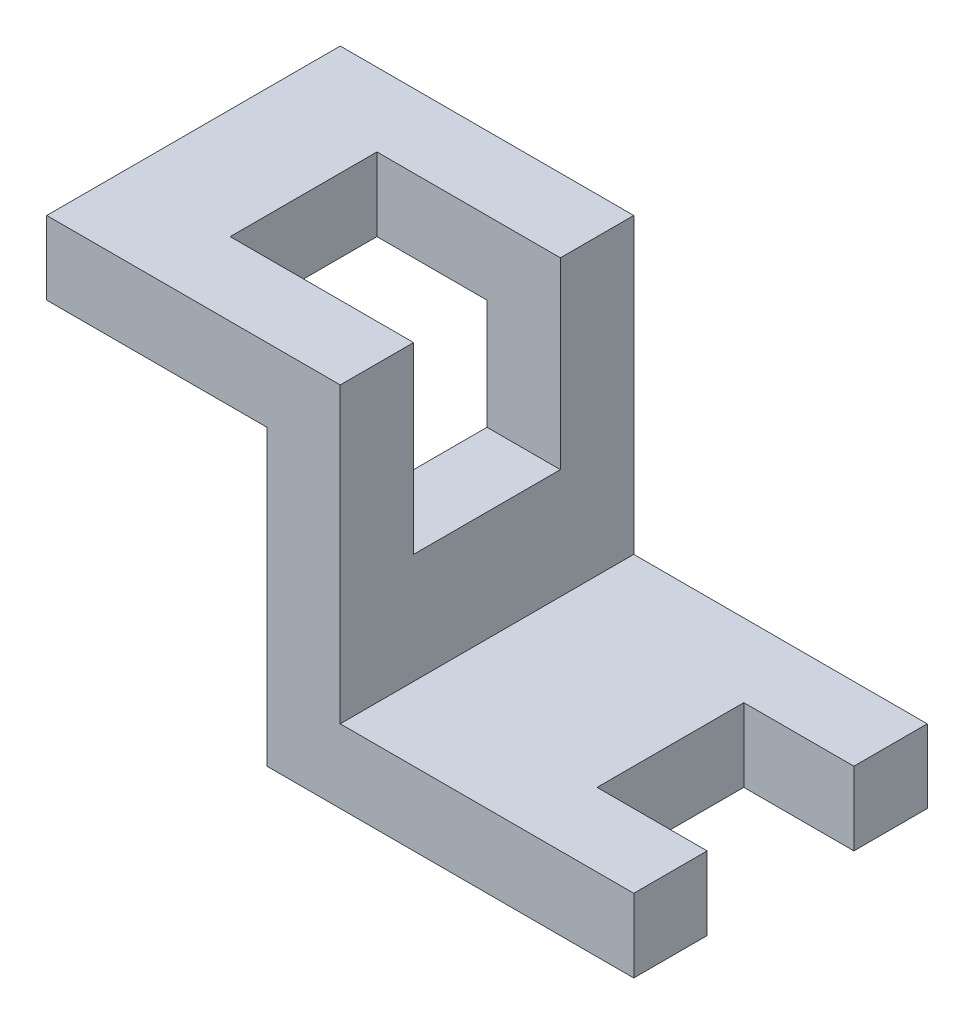
SolidWorks part; units mm, degrees
ref_plane "Front Plane" through (0, 0, 0) normal (0, 0, 1) x (1, 0, 0)
ref_plane "Top Plane" through (0, 0, 0) normal (0, 1, 0) x (1, 0, 0)
ref_plane "Right Plane" through (0, 0, 0) normal (1, 0, 0) x (0, 0, -1)
sketch "Sketch1" plane through (0, 0, 0) normal (0, 0, 1) x (1, 0, 0)
  line L0 (-50.7931, 82.2759) -> (-10.7931, 82.2759)
  line L1 (-10.7931, 82.2759) -> (-10.7931, 42.2759)
  line L2 (-10.7931, 42.2759) -> (29.2069, 42.2759)
  line L3 (29.2069, 42.2759) -> (29.2069, 32.2759)
  line L4 (29.2069, 32.2759) -> (-20.7931, 32.2759)
  line L5 (-20.7931, 32.2759) -> (-20.7931, 72.2759)
  line L6 (-20.7931, 72.2759) -> (-50.7931, 72.2759)
  line L7 (-50.7931, 72.2759) -> (-50.7931, 82.2759)
  dimension "D1" = 40
  dimension "D2" = 50
  dimension "D3" = 40
  dimension "D4" = 30
  dimension "D5" = 10
  dimension "D6" = 10
extrude "Boss-Extrude1" add sketch "Sketch1" along normal blind 40
sketch "Sketch2" plane through (0, 42.2759, 0) normal (0, 1, 0) x (1, 0, 0)
  line L0 (29.2069, -10) -> (14.2069, -10)
  line L1 (29.2069, -40) -> (29.2069, 0) construction
  line L2 (14.2069, -10) -> (14.2069, -30)
  line L3 (14.2069, -30) -> (29.2069, -30)
  line L4 (29.2069, -10) -> (29.2069, -30)
  line L5 (29.2069, 0) -> (-10.7931, 0) construction
  dimension "D1" = 20
  dimension "D2" = 10
  dimension "D3" = 15
extrude "Cut-Extrude1" cut sketch "Sketch2" against normal blind 40
sketch "Sketch3" plane through (0, 82.2759, 0) normal (0, 1, 0) x (1, 0, 0)
  line L0 (-10.7931, -40) -> (-10.7931, 0) construction
  line L1 (-10.7931, -10) -> (-35.7931, -10)
  line L2 (-10.7931, -10) -> (-10.7931, -30)
  line L3 (-10.7931, -30) -> (-35.7931, -30)
  line L4 (-35.7931, -10) -> (-35.7931, -30)
  line L5 (-10.7931, 0) -> (-50.7931, 0) construction
  line L6 (-20.7931, -10) -> (-10.7931, -10)
  line L7 (-20.7931, -10) -> (-20.7931, -30)
  line L8 (-20.7931, -30) -> (-10.7931, -30)
  line L9 (-10.7931, -10) -> (-10.7931, -30)
  line M12 (-10.7931, -40) -> (-10.7931, 0)
  dimension "D1" = 25
  dimension "D2" = 20
  dimension "D3" = 10
  dimension "D4" = 10
extrude "Cut-Extrude2" cut sketch "Sketch3" against normal blind 25 contours L7 L1 L4 L3 | L1 L7 L3 M12
